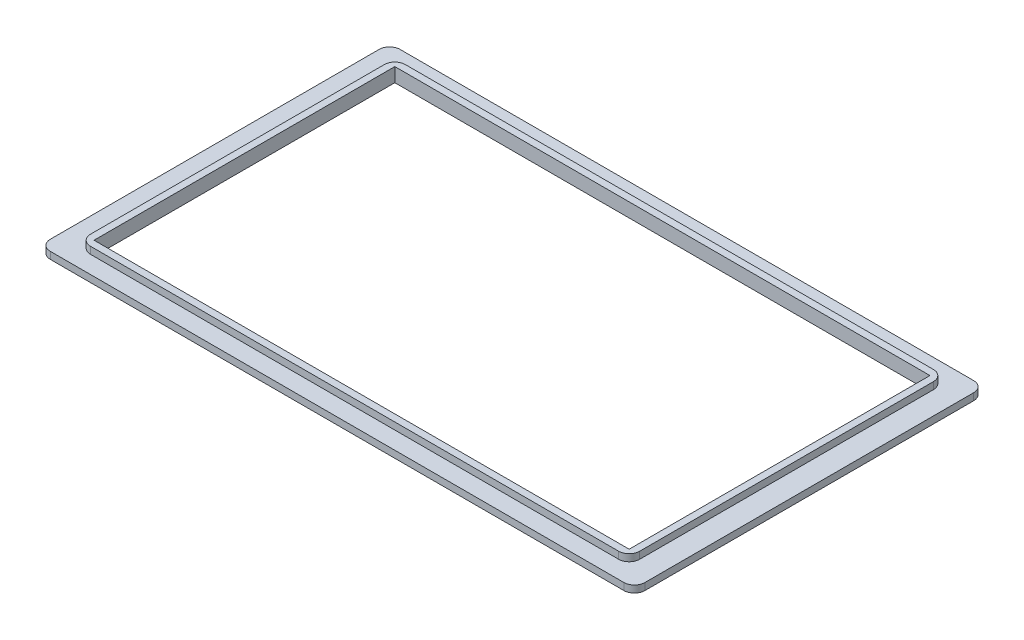
SolidWorks part; units mm, degrees
ref_plane "Front Plane" through (0, 0, 0) normal (0, 0, 1) x (1, 0, 0)
ref_plane "Top Plane" through (0, 0, 0) normal (0, 1, 0) x (1, 0, 0)
ref_plane "Right Plane" through (0, 0, 0) normal (1, 0, 0) x (0, 0, -1)
sketch "Esquisse3" plane through (0, 0, 0) normal (0, 1, 0) x (1, 0, 0)
  line L1 (-85, 50) -> (85, 50)
  line L2 (-85, 50) -> (-85, -50)
  line L3 (-85, -50) -> (85, -50)
  line L4 (85, 50) -> (85, -50)
  line L5 (-85, 50) -> (85, -50) construction
  line L6 (-85, -50) -> (85, 50) construction
  point P0 (0, 0)
extrude "Boss.-Extru.2" add sketch "Esquisse3" along normal blind 2
sketch "Esquisse5" plane through (0, 2, 0) normal (0, 1, 0) x (1, 0, 0)
  line L1 (-78.5, 45) -> (78.5, 45)
  line L2 (-78.5, 45) -> (-78.5, -45)
  line L3 (-78.5, -45) -> (78.5, -45)
  line L4 (78.5, 45) -> (78.5, -45)
  line L5 (-78.5, 45) -> (78.5, -45) construction
  line L6 (-78.5, -45) -> (78.5, 45) construction
  point P0 (0, 0)
extrude "Boss.-Extru.3" add sketch "Esquisse5" along normal blind 2
sketch "Esquisse4" plane through (0, 2, 0) normal (0, 1, 0) x (1, 0, 0)
  line L1 (-76.5, 43) -> (76.5, 43)
  line L2 (-76.5, 43) -> (-76.5, -43)
  line L3 (-76.5, -43) -> (76.5, -43)
  line L4 (76.5, 43) -> (76.5, -43)
  line L5 (-76.5, 43) -> (76.5, -43) construction
  line L6 (-76.5, -43) -> (76.5, 43) construction
  point P0 (0, 0)
extrude "Enlèv. mat.-Extru.1" cut sketch "Esquisse4" against normal through all both and the other way through all
fillet "Congé1" radius 3 8 edges at (-85, 1, 50) (-78.5, 3, 45) (85, 1, 50) (78.5, 3, 45) (85, 1, -50) (78.5, 3, -45) (-78.5, 3, -45) (-85, 1, -50)
sketch "Esquisse7" plane through (0, 0, 0) normal (0, -1, 0) x (-1, 0, 0)
  line L1 (9.5, -49.5626) -> (-9.5, -49.5626)
  line L2 (9.5, -49.5626) -> (9.5, -44.0621)
  line L3 (9.5, -44.0621) -> (-9.5, -44.0621)
  line L4 (-9.5, -49.5626) -> (-9.5, -44.0621)
extrude "Enlèv. mat.-Extru.3" cut sketch "Esquisse7" against normal blind 1 contours L1 L4 L3 L2
sketch "Esquisse10" plane through (0, 1, 0) normal (0, -1, 0) x (1, 0, 0)
  text T0 "F4DEB" font "Century Gothic" height in points 18
extrude "Boss.-Extru.5" add sketch "Esquisse10" along normal blind 1
